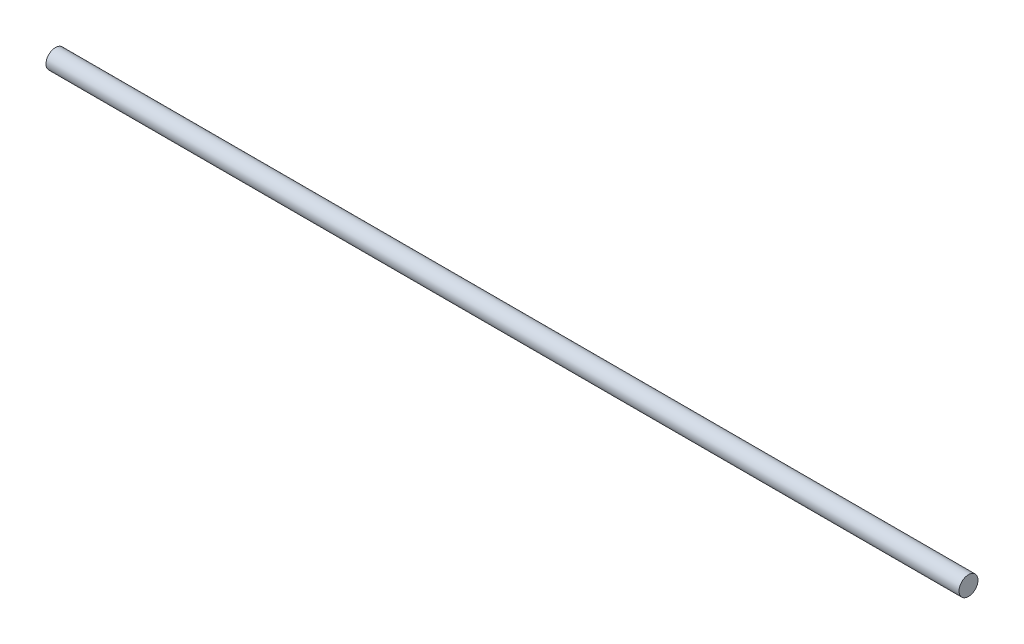
SolidWorks part; units mm, degrees
ref_plane "前视基准面" through (0, 0, 0) normal (0, 0, 1) x (1, 0, 0)
ref_plane "上视基准面" through (0, 0, 0) normal (0, 1, 0) x (1, 0, 0)
ref_plane "右视基准面" through (0, 0, 0) normal (1, 0, 0) x (0, 0, -1)
sketch "草图1" plane through (0, 0, 0) normal (1, 0, 0) x (0, 0, -1)
  circle A0 centre (0, 0) radius 4
  dimension "D1" = 8
extrude "凸台-拉伸1" add sketch "草图1" along normal blind 385
